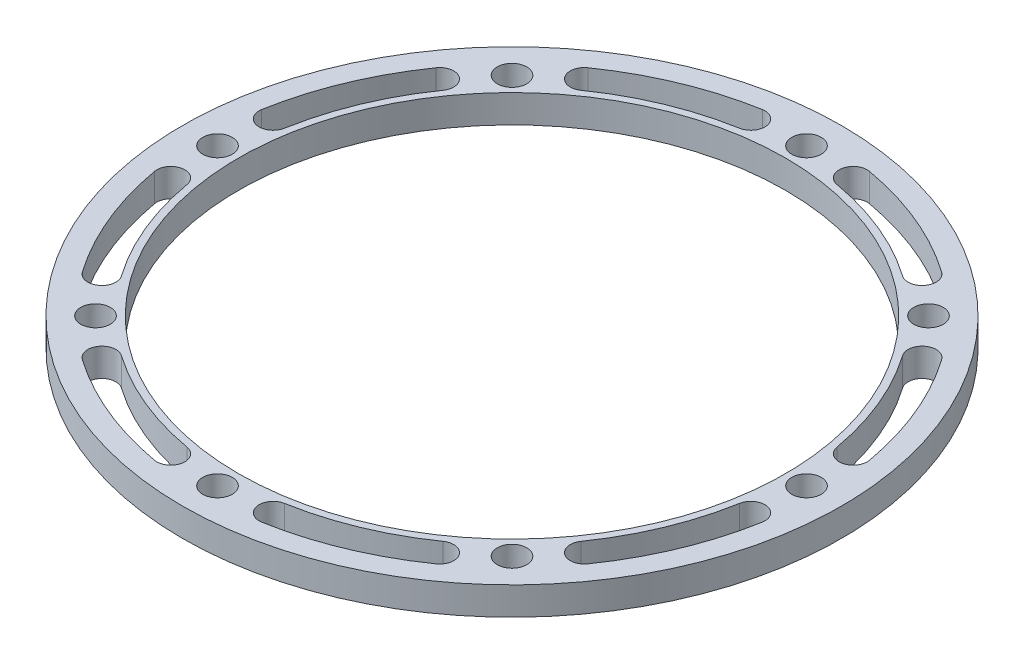
SolidWorks part; units mm, degrees
material "6061-T6 (SS)"
ref_plane "前视基准面" through (0, 0, 0) normal (0, 0, 1) x (1, 0, 0)
ref_plane "上视基准面" through (0, 0, 0) normal (0, 1, 0) x (1, 0, 0)
ref_plane "右视基准面" through (0, 0, 0) normal (1, 0, 0) x (0, 0, -1)
sketch "草图1" plane through (0, 0, 0) normal (0, 0, 1) x (1, 0, 0)
  line L0 (0, 0) -> (0, 24.7963) construction
  line L1 (-39, 0) -> (-47, 0)
  line L2 (-47, 0) -> (-47, 4)
  line L3 (-47, 4) -> (-39, 4)
  line L4 (-39, 4) -> (-39, 0)
  dimension "D1" = 94
  dimension "D2" = 78
  dimension "D3" = 4
revolve "旋转1" add sketch "草图1" angle 360 about L0
sketch "草图2" plane through (0, 0, 0) normal (0, -1, 0) x (1, 0, 0)
  circle A0 centre (0, 0) radius 42 construction
  circle A1 centre (0, 42) radius 2.1
  circle A2 centre (29.6985, 29.6985) radius 2.1
  circle A3 centre (42, 0) radius 2.1
  circle A4 centre (29.6985, -29.6985) radius 2.1
  circle A5 centre (0, -42) radius 2.1
  circle A6 centre (-29.6985, -29.6985) radius 2.1
  circle A7 centre (-42, 0) radius 2.1
  circle A8 centre (-29.6985, 29.6985) radius 2.1
  point P22 (0, 0)
  dimension "D1" = 84
  dimension "D2" = 4.2
  dimension "D3" = 8
extrude "切除-拉伸1" cut sketch "草图2" against normal blind 10
sketch "草图3" plane through (0, 4, 0) normal (0, 1, 0) x (1, 0, 0)
  line L0 (0, 0) -> (16.0727, 38.8029) construction
  line L1 (0, 0) -> (0, 42) construction
  line L2 (7.2932, 41.3619) -> (0, 0) construction
  line L3 (0, 0) -> (24.0902, 34.4044) construction
  circle A0 centre (0, 0) radius 42 construction
  arc A1 (24.0902, 34.4044) -> (7.2932, 41.3619) centre (0, 0) ccw construction
  arc A2 (25.2374, 36.0427) -> (7.6405, 43.3315) centre (0, 0) ccw
  arc A3 (22.9431, 32.7661) -> (6.9459, 39.3923) centre (0, 0) ccw
  arc A4 (22.9431, 32.7661) -> (25.2374, 36.0427) centre (24.0902, 34.4044) ccw
  arc A5 (7.6405, 43.3315) -> (6.9459, 39.3923) centre (7.2932, 41.3619) ccw
  arc A6 (41.3619, 7.2932) -> (34.4044, 24.0902) centre (0, 0) ccw construction
  arc A7 (43.3315, 7.6405) -> (36.0427, 25.2374) centre (0, 0) ccw
  arc A8 (39.3923, 6.9459) -> (32.7661, 22.9431) centre (0, 0) ccw
  arc A9 (39.3923, 6.9459) -> (43.3315, 7.6405) centre (41.3619, 7.2932) ccw
  arc A10 (36.0427, 25.2374) -> (32.7661, 22.9431) centre (34.4044, 24.0902) ccw
  arc A11 (34.4044, -24.0902) -> (41.3619, -7.2932) centre (0, 0) ccw construction
  arc A12 (36.0427, -25.2374) -> (43.3315, -7.6405) centre (0, 0) ccw
  arc A13 (32.7661, -22.9431) -> (39.3923, -6.9459) centre (0, 0) ccw
  arc A14 (32.7661, -22.9431) -> (36.0427, -25.2374) centre (34.4044, -24.0902) ccw
  arc A15 (43.3315, -7.6405) -> (39.3923, -6.9459) centre (41.3619, -7.2932) ccw
  arc A16 (7.2932, -41.3619) -> (24.0902, -34.4044) centre (0, 0) ccw construction
  arc A17 (7.6405, -43.3315) -> (25.2374, -36.0427) centre (0, 0) ccw
  arc A18 (6.9459, -39.3923) -> (22.9431, -32.7661) centre (0, 0) ccw
  arc A19 (6.9459, -39.3923) -> (7.6405, -43.3315) centre (7.2932, -41.3619) ccw
  arc A20 (25.2374, -36.0427) -> (22.9431, -32.7661) centre (24.0902, -34.4044) ccw
  arc A21 (-24.0902, -34.4044) -> (-7.2932, -41.3619) centre (0, 0) ccw construction
  arc A22 (-25.2374, -36.0427) -> (-7.6405, -43.3315) centre (0, 0) ccw
  arc A23 (-22.9431, -32.7661) -> (-6.9459, -39.3923) centre (0, 0) ccw
  arc A24 (-22.9431, -32.7661) -> (-25.2374, -36.0427) centre (-24.0902, -34.4044) ccw
  arc A25 (-7.6405, -43.3315) -> (-6.9459, -39.3923) centre (-7.2932, -41.3619) ccw
  arc A26 (-41.3619, -7.2932) -> (-34.4044, -24.0902) centre (0, 0) ccw construction
  arc A27 (-43.3315, -7.6405) -> (-36.0427, -25.2374) centre (0, 0) ccw
  arc A28 (-39.3923, -6.9459) -> (-32.7661, -22.9431) centre (0, 0) ccw
  arc A29 (-39.3923, -6.9459) -> (-43.3315, -7.6405) centre (-41.3619, -7.2932) ccw
  arc A30 (-36.0427, -25.2374) -> (-32.7661, -22.9431) centre (-34.4044, -24.0902) ccw
  arc A31 (-34.4044, 24.0902) -> (-41.3619, 7.2932) centre (0, 0) ccw construction
  arc A32 (-36.0427, 25.2374) -> (-43.3315, 7.6405) centre (0, 0) ccw
  arc A33 (-32.7661, 22.9431) -> (-39.3923, 6.9459) centre (0, 0) ccw
  arc A34 (-32.7661, 22.9431) -> (-36.0427, 25.2374) centre (-34.4044, 24.0902) ccw
  arc A35 (-43.3315, 7.6405) -> (-39.3923, 6.9459) centre (-41.3619, 7.2932) ccw
  arc A36 (-7.2932, 41.3619) -> (-24.0902, 34.4044) centre (0, 0) ccw construction
  arc A37 (-7.6405, 43.3315) -> (-25.2374, 36.0427) centre (0, 0) ccw
  arc A38 (-6.9459, 39.3923) -> (-22.9431, 32.7661) centre (0, 0) ccw
  arc A39 (-6.9459, 39.3923) -> (-7.6405, 43.3315) centre (-7.2932, 41.3619) ccw
  arc A40 (-25.2374, 36.0427) -> (-22.9431, 32.7661) centre (-24.0902, 34.4044) ccw
  point P8 (16.0727, 38.8029)
  point P21 (38.8029, 16.0727)
  point P28 (38.8029, -16.0727)
  point P35 (16.0727, -38.8029)
  point P42 (-16.0727, -38.8029)
  point P49 (-38.8029, -16.0727)
  point P56 (-38.8029, 16.0727)
  point P63 (-16.0727, 38.8029)
  point P68 (0, 0)
  dimension "D3" = 2
  dimension "D1" = 22.5
  dimension "D2" = 25
  dimension "D4" = 8
extrude "切除-拉伸2" cut sketch "草图3" against normal through all
